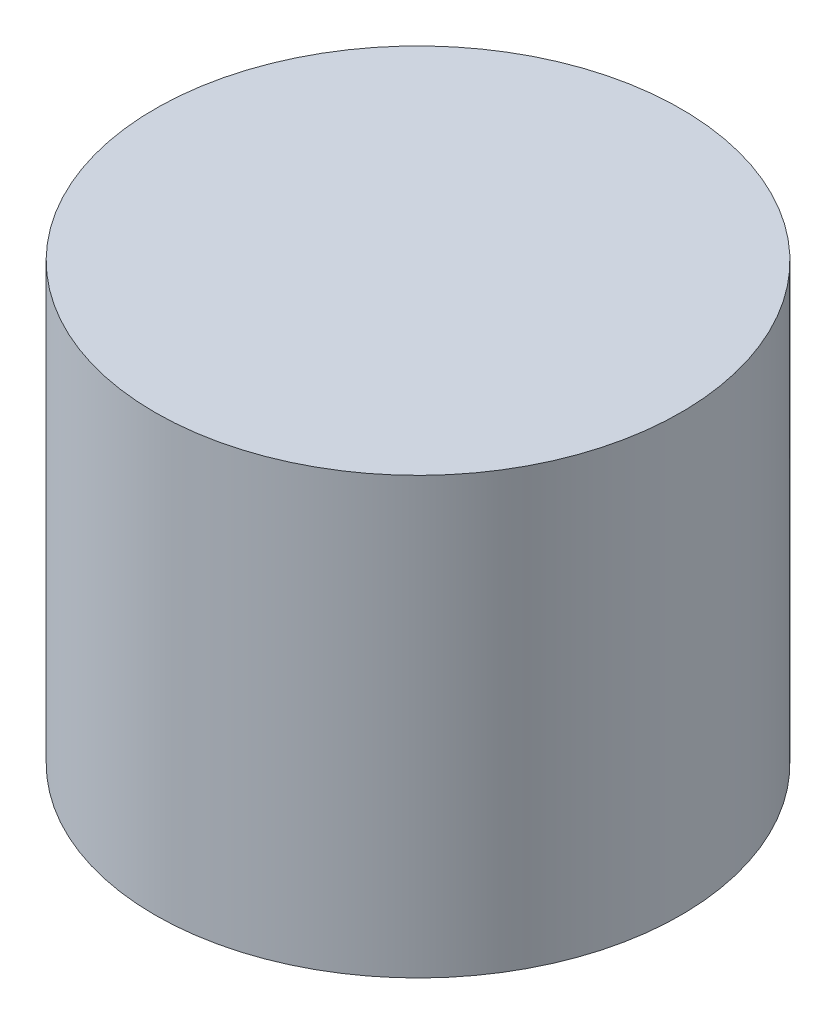
SolidWorks part; units mm, degrees
ref_plane "Front Plane" through (0, 0, 0) normal (0, 0, 1) x (1, 0, 0)
ref_plane "Top Plane" through (0, 0, 0) normal (0, 1, 0) x (1, 0, 0)
ref_plane "Right Plane" through (0, 0, 0) normal (1, 0, 0) x (0, 0, -1)
sketch "Sketch1" plane through (0, 0, 0) normal (0, 1, 0) x (1, 0, 0)
  circle A0 centre (0, 0) radius 2.9
  dimension "D1" = 5.8
extrude "Boss-Extrude1" add sketch "Sketch1" along normal blind 4.8
